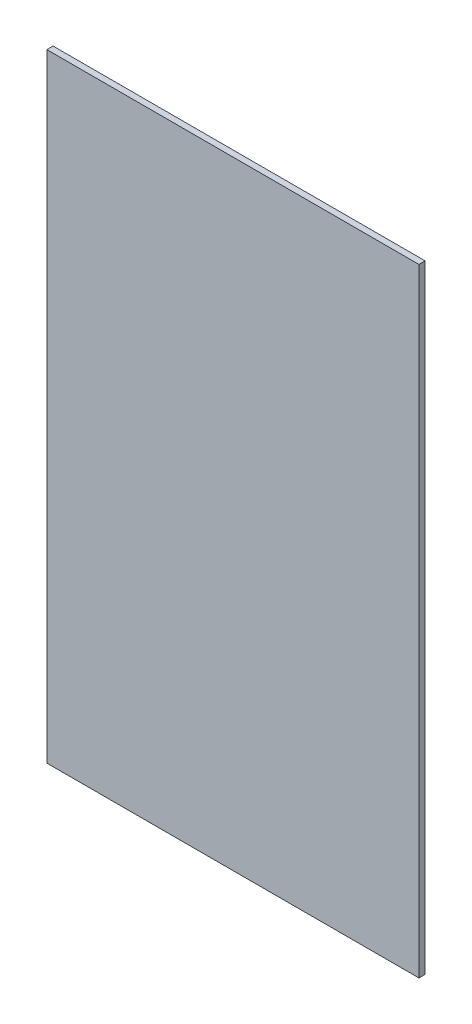
SolidWorks part; units mm, degrees
material "尼龙 6/10"
ref_plane "前视基准面" through (0, 0, 0) normal (0, 0, 1) x (1, 0, 0)
ref_plane "上视基准面" through (0, 0, 0) normal (0, 1, 0) x (1, 0, 0)
ref_plane "右视基准面" through (0, 0, 0) normal (1, 0, 0) x (0, 0, -1)
other "Configuration Table"
sketch "草图1" plane through (0, 0, 0) normal (0, 0, 1) x (1, 0, 0)
  line L1 (-215.1351, 216.8604) -> (264.8649, 216.8604)
  line L2 (-215.1351, 216.8604) -> (-215.1351, -580.1396)
  line L3 (-215.1351, -580.1396) -> (264.8649, -580.1396)
  line L4 (264.8649, 216.8604) -> (264.8649, -580.1396)
  dimension "D1" = 480
  dimension "D2" = 797
extrude "凸台-拉伸1" add sketch "草图1" along normal blind 8
